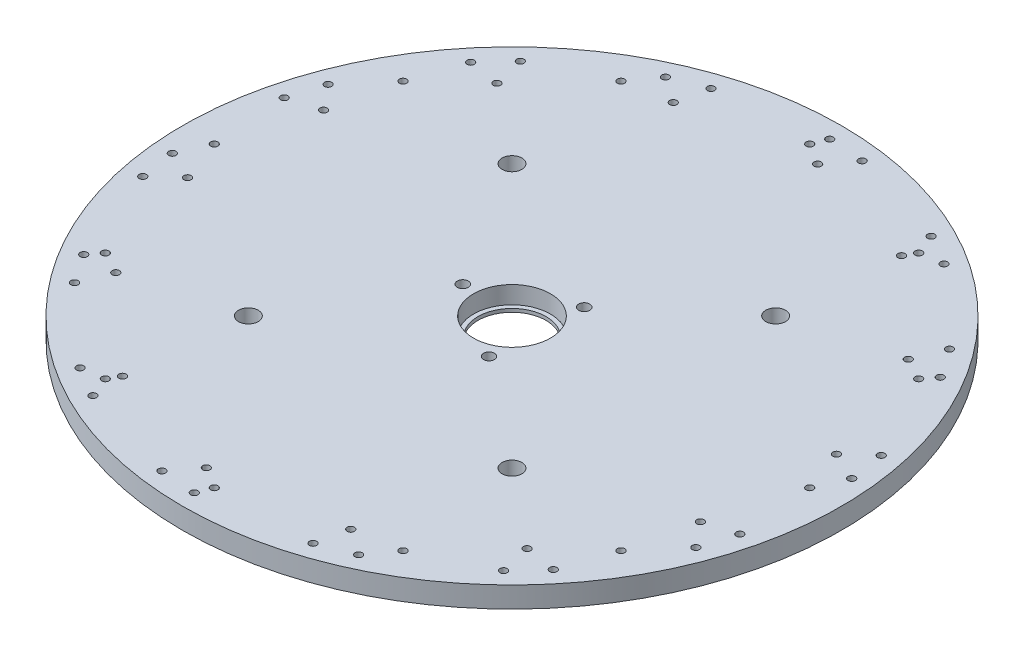
SolidWorks part; units mm, degrees
ref_plane "Front Plane" through (0, 0, 0) normal (0, 0, 1) x (1, 0, 0)
ref_plane "Top Plane" through (0, 0, 0) normal (0, 1, 0) x (1, 0, 0)
ref_plane "Right Plane" through (0, 0, 0) normal (1, 0, 0) x (0, 0, -1)
sketch "Sketch1" plane through (0, 0, 0) normal (0, 1, 0) x (1, 0, 0)
  circle A0 centre (0, 0) radius 150
extrude "Boss-Extrude1" add sketch "Sketch1" along normal blind 9.52
sketch "Sketch2" plane through (0, 9.52, 0) normal (0, 1, 0) x (1, 0, 0)
  circle A0 centre (0, 0) radius 15.5
extrude "Cut-Extrude1" cut sketch "Sketch2" against normal through all
sketch "Sketch3" plane through (0, 9.52, 0) normal (0, 1, 0) x (1, 0, 0)
  circle A0 centre (0, 0) radius 17.505
extrude "Cut-Extrude2" cut sketch "Sketch3" against normal blind 8
sketch "Sketch4" plane through (0, 9.52, 0) normal (0, 1, 0) x (1, 0, 0)
  circle A0 centre (10.7251, -21.1932) radius 2.5
  circle A1 centre (-23.7164, 1.3084) radius 2.5
  circle A2 centre (12.9913, 19.8849) radius 2.5
  circle A3 centre (67.75, -117.3464) radius 1.65
  circle A4 centre (0, -135.5) radius 1.65
  circle A5 centre (-67.75, -117.3464) radius 1.65
  circle A6 centre (-117.3464, -67.75) radius 1.65
  circle A7 centre (-135.5, 0) radius 1.65
  circle A8 centre (-117.3464, 67.75) radius 1.65
  circle A9 centre (-67.75, 117.3464) radius 1.65
  circle A10 centre (0, 135.5) radius 1.65
  circle A11 centre (67.75, 117.3464) radius 1.65
  circle A12 centre (117.3464, 67.75) radius 1.65
  circle A13 centre (135.5, 0) radius 1.65
  circle A14 centre (117.3464, -67.75) radius 1.65
extrude "Cut-Extrude3" cut sketch "Sketch4" against normal through all
sketch "Sketch6" plane through (0, 0, 0) normal (0, -1, 0) x (-1, 0, 0)
  circle A0 centre (-63.9648, 126.7902) radius 1.65
  circle A1 centre (-77.8212, 118.7902) radius 1.65
  circle A2 centre (-64.893, 112.3979) radius 1.65
  circle A3 centre (-9.6989, 129.423) radius 1.65
  circle A4 centre (-2.618, 141.9873) radius 1.65
  circle A5 centre (-18.5733, 140.7916) radius 1.65
  circle A6 centre (59.2472, 129.0621) radius 1.65
  circle A7 centre (44.3532, 134.9075) radius 1.65
  circle A8 centre (47.4161, 120.8143) radius 1.65
  circle A9 centre (109.3778, 90.5745) radius 1.65
  circle A10 centre (98.4951, 102.3033) radius 1.65
  circle A11 centre (95.1398, 88.2769) radius 1.65
  circle A12 centre (133.1287, 49.4367) radius 1.65
  circle A13 centre (124.0199, 38.2551) radius 1.65
  circle A14 centre (137.8448, 34.1476) radius 1.65
  circle A15 centre (141.3946, -13.2214) radius 1.65
  circle A16 centre (128.3363, -19.3436) radius 1.65
  circle A17 centre (139.01, -29.0427) radius 1.65
  circle A18 centre (121.6556, -73.2609) radius 1.65
  circle A19 centre (112.6425, -86.4808) radius 1.65
  circle A20 centre (107.2342, -73.111) radius 1.65
  circle A21 centre (64.893, -112.3979) radius 1.65
  circle A22 centre (63.9648, -126.7902) radius 1.65
  circle A23 centre (77.8212, -118.7902) radius 1.65
  circle A24 centre (9.6989, -129.423) radius 1.65
  circle A25 centre (2.618, -141.9873) radius 1.65
  circle A26 centre (18.5733, -140.7916) radius 1.65
  circle A27 centre (-44.3532, -134.9075) radius 1.65
  circle A28 centre (-59.2472, -129.0621) radius 1.65
  circle A29 centre (-47.4161, -120.8143) radius 1.65
  circle A30 centre (-98.4951, -102.3033) radius 1.65
  circle A31 centre (-109.3778, -90.5745) radius 1.65
  circle A32 centre (-95.1398, -88.2769) radius 1.65
  circle A33 centre (-124.0199, -38.2551) radius 1.65
  circle A34 centre (-137.8448, -34.1476) radius 1.65
  circle A35 centre (-133.1287, -49.4367) radius 1.65
  circle A36 centre (-128.3363, 19.3436) radius 1.65
  circle A37 centre (-141.3946, 13.2214) radius 1.65
  circle A38 centre (-139.01, 29.0427) radius 1.65
  circle A39 centre (-107.2342, 73.111) radius 1.65
  circle A40 centre (-121.6556, 73.2609) radius 1.65
  circle A41 centre (-112.6425, 86.4808) radius 1.65
extrude "Cut-Extrude5" cut sketch "Sketch6" against normal through all
sketch "Sketch7" plane through (0, 9.52, 0) normal (0, 1, 0) x (1, 0, 0)
  circle A8 centre (-60, -60) radius 4.5
  circle A9 centre (60, -60) radius 4.5
  circle A10 centre (60, 60) radius 4.5
  circle A11 centre (-60, 60) radius 4.5
  dimension "D1" = 2
  dimension "D2" = 2
extrude "Cut-Extrude6" cut sketch "Sketch7" against normal through all
